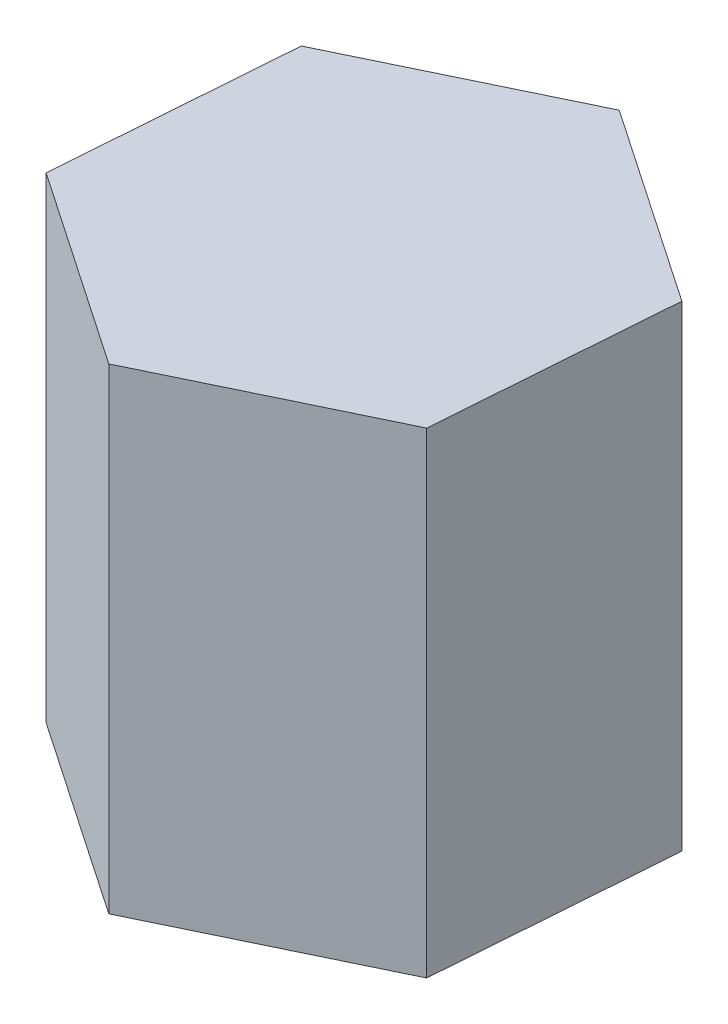
SolidWorks part; units mm, degrees
ref_plane "前视基准面" through (0, 0, 0) normal (0, 0, 1) x (1, 0, 0)
ref_plane "上视基准面" through (0, 0, 0) normal (0, 1, 0) x (1, 0, 0)
ref_plane "右视基准面" through (0, 0, 0) normal (1, 0, 0) x (0, 0, -1)
other "Configuration Table"
sketch "草图1" plane through (0, 0, 0) normal (0, 1, 0) x (1, 0, 0)
  line L1 (16.5266, -11.2637) -> (18.018, 8.6806)
  line L2 (18.018, 8.6806) -> (1.4913, 19.9443)
  line L3 (1.4913, 19.9443) -> (-16.5266, 11.2637)
  line L4 (-16.5266, 11.2637) -> (-18.018, -8.6806)
  line L5 (-18.018, -8.6806) -> (-1.4913, -19.9443)
  line L6 (-1.4913, -19.9443) -> (16.5266, -11.2637)
  circle A0 centre (0, 0) radius 17.3205 construction
  dimension "D1" = 20
extrude "凸台-拉伸1" add sketch "草图1" along normal blind 40
